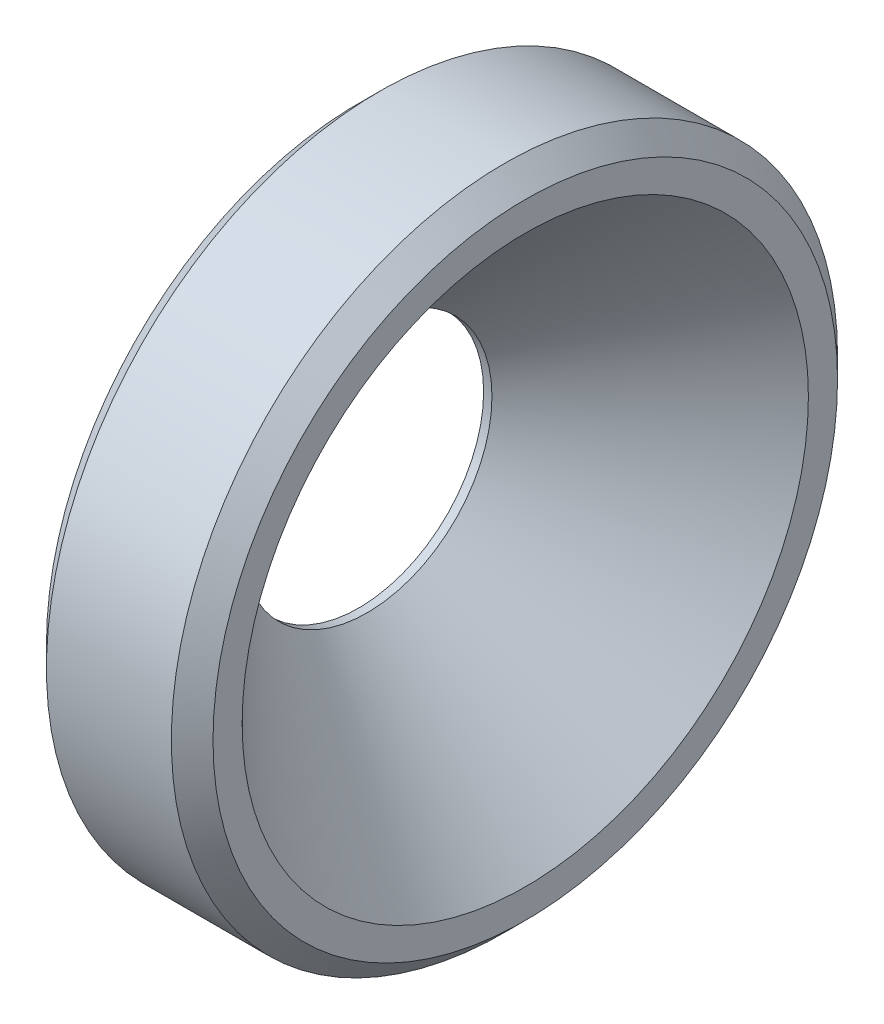
SolidWorks part; units mm, degrees
material "6063-T6"
ref_plane "Front Plane" through (0, 0, 0) normal (0, 0, 1) x (1, 0, 0)
ref_plane "Top Plane" through (0, 0, 0) normal (0, 1, 0) x (1, 0, 0)
ref_plane "Right Plane" through (0, 0, 0) normal (1, 0, 0) x (0, 0, -1)
sketch "Sketch1" plane through (0, 0, 0) normal (1, 0, 0) x (0, 0, -1)
  circle A0 centre (0, 0) radius 4
  circle A1 centre (0, 0) radius 1.5
  dimension "D1" = 8
  dimension "D2" = 3
extrude "Boss-Extrude1" add sketch "Sketch1" along normal blind 2
chamfer "Chamfer1" distance 1.9 angle 45 1 edges at (2, 0, -1.5)
chamfer "Chamfer2" distance 0.25 angle 45 2 edges at (2, 0, -4) (0, 0, -4)
